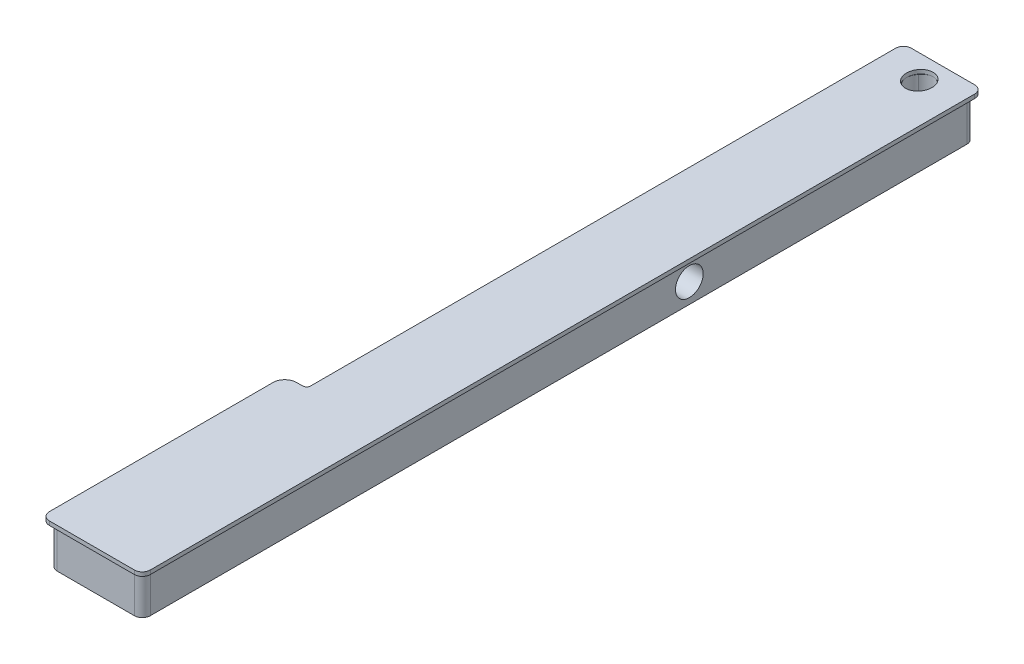
SolidWorks part; units mm, degrees
ref_plane "Plan de face" through (0, 0, 0) normal (0, 0, 1) x (1, 0, 0)
ref_plane "Plan de dessus" through (0, 0, 0) normal (0, 1, 0) x (1, 0, 0)
ref_plane "Plan de droite" through (0, 0, 0) normal (1, 0, 0) x (0, 0, -1)
sketch "Esquisse1" plane through (0, 0, 0) normal (0, 1, 0) x (1, 0, 0)
  line L0 (11.344, -69) -> (-12.136, -69)
  line L1 (11.344, 69) -> (11.344, -69)
  line L3 (-6.636, 69) -> (-6.636, -9.5659)
  line L4 (-6.636, -9.5659) -> (-12.136, -9.5659)
  line L5 (-12.136, -9.5659) -> (-12.136, -69)
  line L6 (-6.636, 69) -> (-6.636, 141)
  line L7 (-6.636, 141) -> (11.344, 141)
  line L8 (11.344, 141) -> (11.344, 69)
  dimension "D1" = 17.98
  dimension "D2" = 5.5
  dimension "D3" = 23.48
extrude "Boss.-Extru.1" add sketch "Esquisse1" along normal blind 10
sketch "Esquisse2" plane through (0, 10, 0) normal (0, 1, 0) x (1, 0, 0)
  line L0 (2.354, 141) -> (2.354, 136) construction
  line L1 (11.344, 141) -> (-6.636, 141) construction
  line L2 (-6.636, 141) -> (-6.636, -9.5659) construction
  ellipse E0 centre (2.354, 136) end of major axis (2.354, 139.5) minor radius 3
  dimension "D1" = 8.99
  dimension "D2" = 5
extrude "Enlèv. mat.-Extru.1" cut sketch "Esquisse2" against normal blind 10
sketch "Esquisse3" plane through (0, 10, 0) normal (0, 1, 0) x (1, 0, 0)
  circle A0 centre (2.354, 136) radius 3.2
extrude "Enlèv. mat.-Extru.2" cut sketch "Esquisse3" against normal blind 10 contours A0
sketch "Esquisse4" plane through (11.344, 0, 0) normal (1, 0, 0) x (0, 0, -1)
  line L0 (141, 5) -> (69, 5) construction
  line L1 (141, 10) -> (141, 0) construction
  circle A0 centre (69, 5) radius 3.5
extrude "Enlèv. mat.-Extru.3" cut sketch "Esquisse4" against normal blind 43
sketch "Esquisse6" plane through (0, 10, 0) normal (0, 1, 0) x (1, 0, 0)
  line L0 (-6.636, 141) -> (-7.3431, 141.7071) construction
  line L1 (11.344, -69) -> (11.344, 141) construction
  line L2 (12.344, 142) -> (-13.136, 142)
  line L3 (12.344, 142) -> (12.344, -70)
  line L4 (12.344, -70) -> (-13.136, -70)
  line L5 (-13.136, 142) -> (-13.136, -70)
  line L6 (11.344, 141) -> (-6.636, 141) construction
  line L8 (-12.136, -69) -> (11.344, -69) construction
  line L9 (-12.136, -9.5659) -> (-12.136, -69) construction
  dimension "D1" = 1
  dimension "D2" = 1
  dimension "D3" = 1
  dimension "D4" = 1
extrude "Boss.-Extru.2" add sketch "Esquisse6" along normal blind 1 contours L5 L4 L3 L2
fillet "Congé1" radius 2 6 edges at (-6.636, 5, -141) (11.344, 5, -141) (11.344, 5, 69) (-12.136, 5, 69) (-6.636, 5, 9.5659) (-12.136, 5, 9.5659)
sketch "Esquisse8" plane through (0, 10, 0) normal (0, -1, 0) x (-1, 0, 0)
  line L0 (11.5502, -10.1517) -> (11.4676, -9.4445) construction
  line L1 (12.136, -11.5659) -> (13.136, -11.5659) construction
  line L2 (13.136, 142) -> (13.136, -70) construction
  line L3 (10.136, -9.5659) -> (10.136, -8.5659) construction
  line L4 (7.2218, -8.9801) -> (7.9289, -8.273) construction
  line L5 (6.636, -7.5659) -> (7.636, -7.5659) construction
  line L6 (8.636, -9.5659) -> (8.636, -8.5659) construction
  line L7 (8.636, -8.5659) -> (10.136, -8.5659)
  line L8 (13.136, -11.5659) -> (13.1426, -11.5659)
  line L9 (13.1426, -11.5659) -> (13.1426, 143.9037)
  line L10 (13.1426, 143.9037) -> (7.636, 143.9037)
  line L11 (7.636, 143.9037) -> (7.636, -7.5659)
  arc A0 (12.136, -11.5659) -> (10.136, -9.5659) centre (10.136, -11.5659) ccw construction
  arc A2 (6.636, -7.5659) -> (8.636, -9.5659) centre (8.636, -7.5659) ccw construction
  arc A3 (13.136, -11.5659) -> (10.136, -8.5659) centre (10.136, -11.5659) ccw
  arc A4 (6.636, -7.5659) -> (8.636, -9.5659) centre (8.636, -7.5659) ccw construction
  arc A5 (7.636, -7.5659) -> (8.636, -8.5659) centre (8.636, -7.5659) ccw
extrude "Enlèv. mat.-Extru.10" cut sketch "Esquisse8" against normal blind 10 contours L11 A5 L7 A3 L8 L9 L10
fillet "Congé4" radius 2 4 edges at (-13.136, 10.5, 70) (12.344, 10.5, 70) (12.344, 10.5, -142) (-7.636, 10.5, -142)
sketch "Esquisse14" plane through (0, 10, 0) normal (0, -1, 0) x (-1, 0, 0)
  circle A0 centre (-2.354, 136) radius 3.2
extrude "Enlèv. mat.-Extru.11" cut sketch "Esquisse14" against normal blind 10
sketch "Esquisse16" plane through (0, 10, 0) normal (0, -1, 0) x (-1, 0, 0)
  arc A0 (-4.7133, 138.1619) -> (-4.7133, 133.8381) centre (-2.354, 136) ccw construction
  ellipse E0 centre (-2.354, 136) end of major axis (-2.354, 132.5) minor radius 3.2
extrude "Enlèv. mat.-Extru.12" cut sketch "Esquisse16" against normal blind 10
